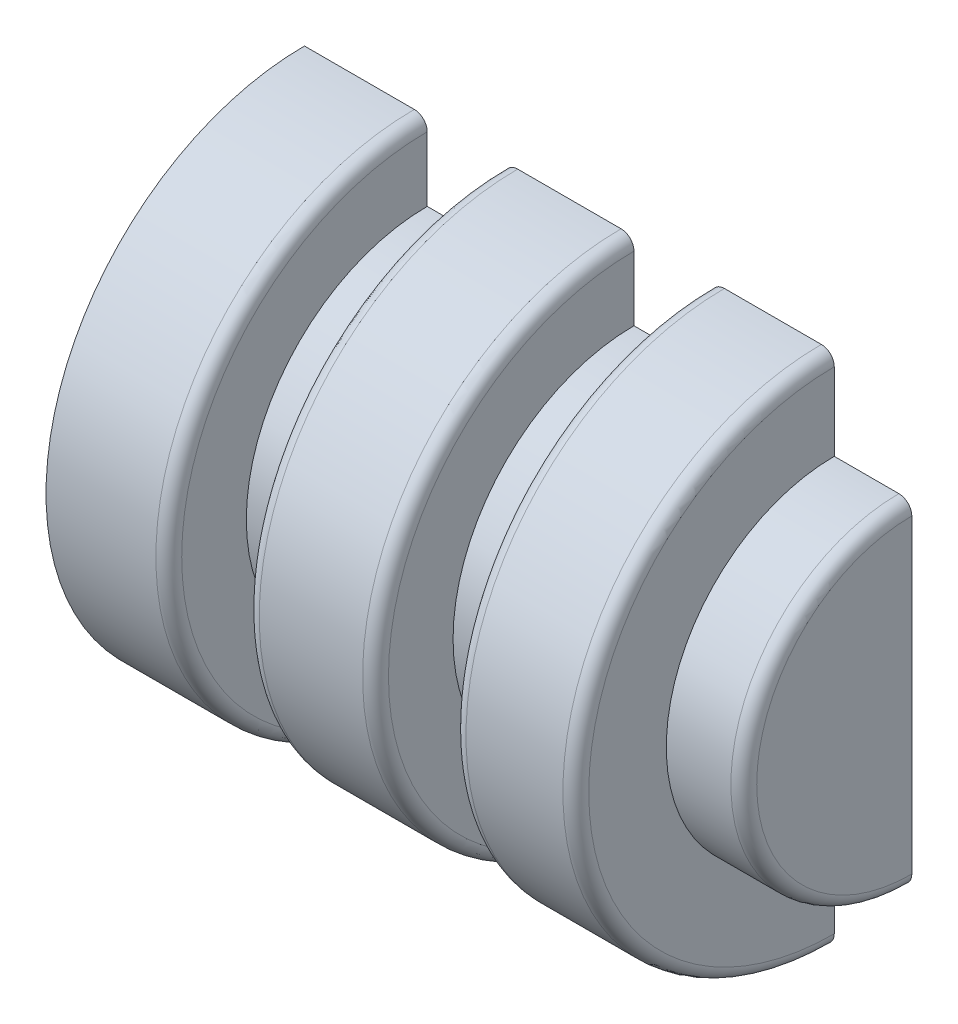
SolidWorks part; units mm, degrees
ref_plane "Front Plane" through (0, 0, 0) normal (0, 0, 1) x (1, 0, 0)
ref_plane "Top Plane" through (0, 0, 0) normal (0, 1, 0) x (1, 0, 0)
ref_plane "Right Plane" through (0, 0, 0) normal (1, 0, 0) x (0, 0, -1)
sketch "Sketch1" plane through (0, 0, 0) normal (1, 0, 0) x (0, 0, -1)
  circle A0 centre (0, 0) radius 10
  dimension "D1" = 20
extrude "Boss-Extrude1" add sketch "Sketch1" along normal blind 4.75
sketch "Sketch4" plane through (4.75, 0, 0) normal (1, 0, 0) x (0, 0, -1)
  circle A0 centre (0, 0) radius 6.5
  dimension "D1" = 13
extrude "Boss-Extrude2" add sketch "Sketch4" along normal blind 3
sketch "Sketch5" plane through (0, 0, 0) normal (-1, 0, 0) x (0, 0, 1)
  circle A0 centre (0, 0) radius 7
  dimension "D1" = 14
extrude "Boss-Extrude3" add sketch "Sketch5" along normal blind 3
fillet "Fillet1" radius 0.5 1 edges at (7.75, 0, -6.5)
sketch "Sketch6" plane through (-3, 0, 0) normal (-1, 0, 0) x (0, 0, 1)
  circle A0 centre (0, 0) radius 10
  dimension "D1" = 20
extrude "Boss-Extrude4" add sketch "Sketch6" along normal blind 5
sketch "Sketch7" plane through (-8, 0, 0) normal (-1, 0, 0) x (0, 0, 1)
  circle A0 centre (0, 0) radius 7
  dimension "D1" = 14
extrude "Boss-Extrude5" add sketch "Sketch7" along normal blind 3
sketch "Sketch9" plane through (-11, 0, 0) normal (-1, 0, 0) x (0, 0, 1)
  circle A0 centre (0, 0) radius 10
  dimension "D1" = 20
extrude "Boss-Extrude6" add sketch "Sketch9" along normal blind 4.75
fillet "Fillet2" radius 0.5 5 edges at (-11, 0, 10) (-8, 0, 10) (-3, 0, 10) (0, 0, -10) (4.75, 0, -10)
sketch "Sketch10" plane through (0, 0, 0) normal (0, 0, 1) x (1, 0, 0)
  line L1 (-15.75, 10) -> (8.1834, 10)
  line L2 (-15.75, 10) -> (-15.75, -10)
  line L3 (-15.75, -10) -> (8.1834, -10)
  line L4 (8.1834, 10) -> (8.1834, -10)
extrude "Cut-Extrude1" cut sketch "Sketch10" against normal blind 20
sketch "Sketch11" plane through (-15.75, 0, 0) normal (-1, 0, 0) x (0, 0, 1)
  line L0 (0, 10) -> (0, -10) construction
  line L1 (0, 2.75) -> (0, -2.75)
  arc A0 (0, -2.75) -> (0, 2.75) centre (0, 0) ccw
  dimension "D1" = 5.5
extrude "Cut-Extrude2" cut sketch "Sketch11" against normal blind 5
